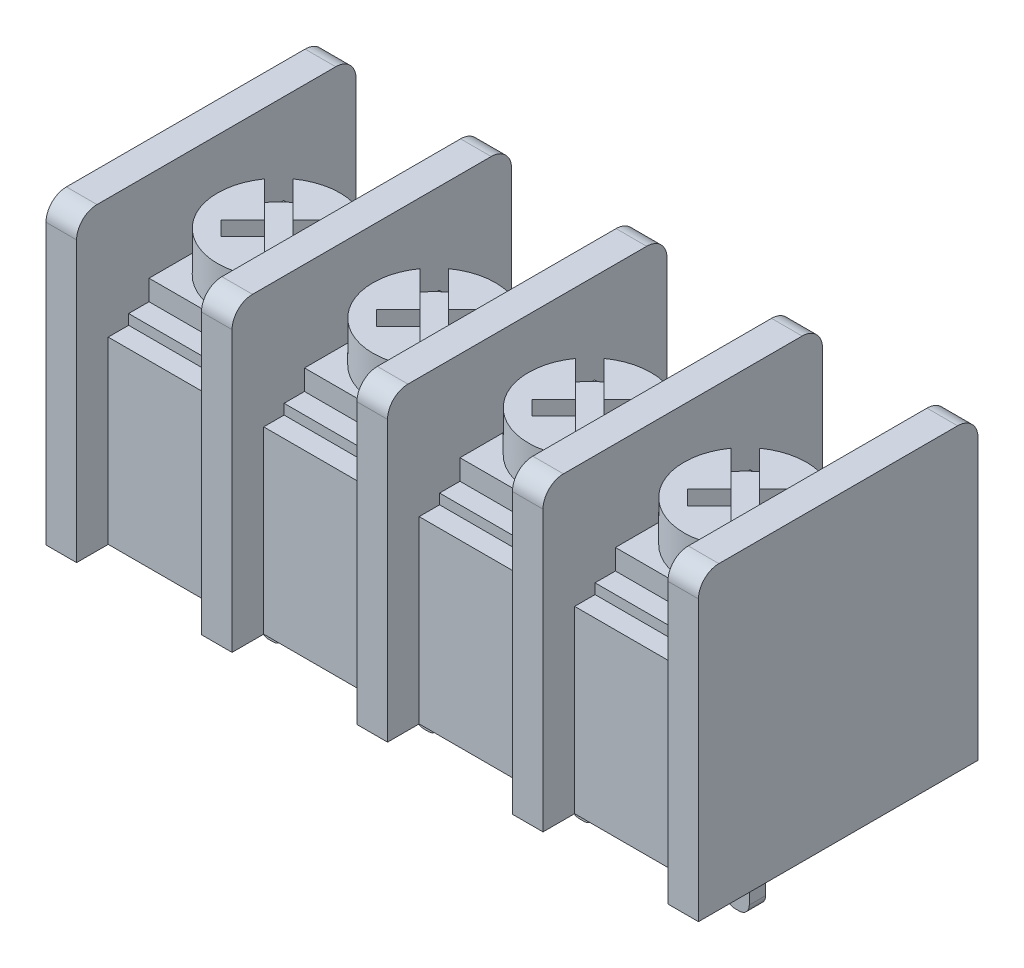
SolidWorks part; units mm, degrees
ref_plane "Alzado" through (0, 0, 0) normal (0, 0, 1) x (1, 0, 0)
ref_plane "Planta" through (0, 0, 0) normal (0, 1, 0) x (1, 0, 0)
ref_plane "Vista lateral" through (0, 0, 0) normal (1, 0, 0) x (0, 0, -1)
sketch "Croquis1" plane through (0, 0, 0) normal (0, 1, 0) x (1, 0, 0)
  line L1 (-0.75, -6.85) -> (0.75, -6.85)
  line L2 (-0.75, -6.85) -> (-0.75, 6.85)
  line L3 (-0.75, 6.85) -> (0.75, 6.85)
  line L4 (0.75, -6.85) -> (0.75, 6.85)
  line L5 (-0.75, -6.85) -> (0.75, 6.85) construction
  line L6 (-0.75, 6.85) -> (0.75, -6.85) construction
  point P0 (0, 0)
  dimension "D1" = 13.7
  dimension "D2" = 1.5
extrude "Saliente-Extruir1" add sketch "Croquis1" along normal blind 14.7
fillet "Redondeo1" radius 1 2 edges at (0, 14.7, -6.85) (0, 14.7, 6.85)
pattern_linear "MatrizL1" count 3 spacing 7.62 along (1, 0, 0) count 3 spacing 7.62 along (-1, 0, 0) of bodies 101
sketch "Croquis2" plane through (0, 0, 0) normal (0, 1, 0) x (1, 0, 0)
  line L0 (-15.99, 6.85) -> (-15.99, -6.85) construction
  line L1 (-15.99, -5.3) -> (15.99, -5.3)
  line L2 (-15.99, -5.3) -> (-15.99, 5.3)
  line L3 (-15.99, 5.3) -> (15.99, 5.3)
  line L4 (15.99, -5.3) -> (15.99, 5.3)
  line L5 (-15.99, -5.3) -> (15.99, 5.3) construction
  line L6 (-15.99, 5.3) -> (15.99, -5.3) construction
  point P0 (0, 0)
  dimension "D1" = 10.6
extrude "Saliente-Extruir2" add sketch "Croquis2" along normal blind 8.8
sketch "Croquis4" plane through (0, 0, 0) normal (0, -1, 0) x (1, 0, 0)
  line L1 (-4.41, -0.4) -> (-3.21, -0.4)
  line L2 (-4.41, -0.4) -> (-4.41, 0.4)
  line L3 (-4.41, 0.4) -> (-3.21, 0.4)
  line L4 (-3.21, -0.4) -> (-3.21, 0.4)
  line L5 (-4.41, -0.4) -> (-3.21, 0.4) construction
  line L6 (-4.41, 0.4) -> (-3.21, -0.4) construction
  point P0 (-3.81, 0)
  point P5 (0, 0)
  dimension "D1" = 1.2
  dimension "D2" = 0.8
  dimension "D3" = 3.81
extrude "Saliente-Extruir5" add sketch "Croquis4" along normal blind 5
fillet "Redondeo4" radius 0.5 2 edges at (-3.21, -5, 0) (-4.41, -5, 0)
pattern_linear "MatrizL2" count 2 spacing 7.62 along (-1, 0, 0) count 3 spacing 7.62 along (1, 0, 0) of "Redondeo4", "Saliente-Extruir5"
sketch "Croquis5" plane through (0, 8.8, 0) normal (0, 1, 0) x (1, 0, 0)
  line L0 (-0.75, 5.85) -> (-0.75, -5.85) construction
  line L1 (-6.87, -4.3) -> (-0.75, -4.3)
  line L2 (-6.87, -4.3) -> (-6.87, 4.3)
  line L3 (-6.87, 4.3) -> (-0.75, 4.3)
  line L4 (-0.75, -4.3) -> (-0.75, 4.3)
  line L5 (-6.87, -4.3) -> (-0.75, 4.3) construction
  line L6 (-6.87, 4.3) -> (-0.75, -4.3) construction
  line L7 (-6.87, -5.85) -> (-6.87, 5.85) construction
  line L8 (-0.75, 5.3) -> (-6.87, 5.3) construction
  point P0 (-3.81, 0)
  point P5 (0, 0)
  point P7 (0, 0)
  dimension "D1" = 1
extrude "Saliente-Extruir6" add sketch "Croquis5" along normal blind 0.5
sketch "Croquis6" plane through (0, 9.3, 0) normal (0, 1, 0) x (1, 0, 0)
  line L0 (-0.75, 5.85) -> (-0.75, -5.85) construction
  line L1 (-6.87, -3.3) -> (-0.75, -3.3)
  line L2 (-6.87, -3.3) -> (-6.87, 3.3)
  line L3 (-6.87, 3.3) -> (-0.75, 3.3)
  line L4 (-0.75, -3.3) -> (-0.75, 3.3)
  line L5 (-6.87, -3.3) -> (-0.75, 3.3) construction
  line L6 (-6.87, 3.3) -> (-0.75, -3.3) construction
  line L7 (-6.87, -5.85) -> (-6.87, 5.85) construction
  line L8 (-0.75, 4.3) -> (-6.87, 4.3) construction
  point P0 (-3.81, 0)
  point P5 (0, 0)
  dimension "D1" = 1
extrude "Saliente-Extruir7" add sketch "Croquis6" along normal blind 1
sketch "Croquis7" plane through (0, 10.3, 0) normal (0, 1, 0) x (1, 0, 0)
  line L0 (-0.75, 3.3) -> (-6.87, 3.3) construction
  circle A0 centre (-3.81, 0) radius 3
  point P2 (0, 0)
  point P5 (0, 0)
  point P6 (0, 0)
  point P9 (-3.81, 3.3)
  dimension "D1" = 6
extrude "Saliente-Extruir14" add sketch "Croquis7" along normal blind 2 contours A0
sketch "Croquis13" plane through (0, 12.3, 0) normal (0, 1, 0) x (1, 0, 0)
  line L1 (-1.8301, -2.687) -> (-1.123, -1.9799)
  line L2 (-1.8301, -2.687) -> (-6.497, 1.9799)
  line L3 (-6.497, 1.9799) -> (-5.7899, 2.687)
  line L4 (-1.123, -1.9799) -> (-5.7899, 2.687)
  line L5 (-4.31, -3.3) -> (-3.31, 3.3) construction
  line L6 (-4.31, 3.3) -> (-3.31, -3.3) construction
  line L9 (-5.5778, -1.0607) -> (-2.7493, 1.7678)
  line L10 (-5.5778, -1.0607) -> (-4.8707, -1.7678)
  line L11 (-4.8707, -1.7678) -> (-2.0422, 1.0607)
  line L12 (-2.7493, 1.7678) -> (-2.0422, 1.0607)
  line L13 (-5.81, 0.5) -> (-1.81, -0.5) construction
  line L14 (-5.81, -0.5) -> (-1.81, 0.5) construction
  point P0 (-3.81, 0)
  point P11 (-3.81, 0)
  circle M5 centre (-3.81, 0) radius 3
  dimension "D1" = 3.81
  dimension "D2" = 1
  dimension "D3" = 1
  dimension "D4" = 4
extrude "Cortar-Extruir2" cut sketch "Croquis13" against normal blind 1 contours L2 L9 L4 M5 | L12 L9 L4 L11 | L10 L11 L2 L9 | L2 L11 L4 L9 | L11 L2 L4 M5
pattern_linear "MatrizL3" count 2 spacing 7.62 along (-1, 0, 0) count 3 spacing 7.62 along (1, 0, 0) of "Saliente-Extruir6", "Cortar-Extruir2", "Saliente-Extruir14", "Saliente-Extruir7"
